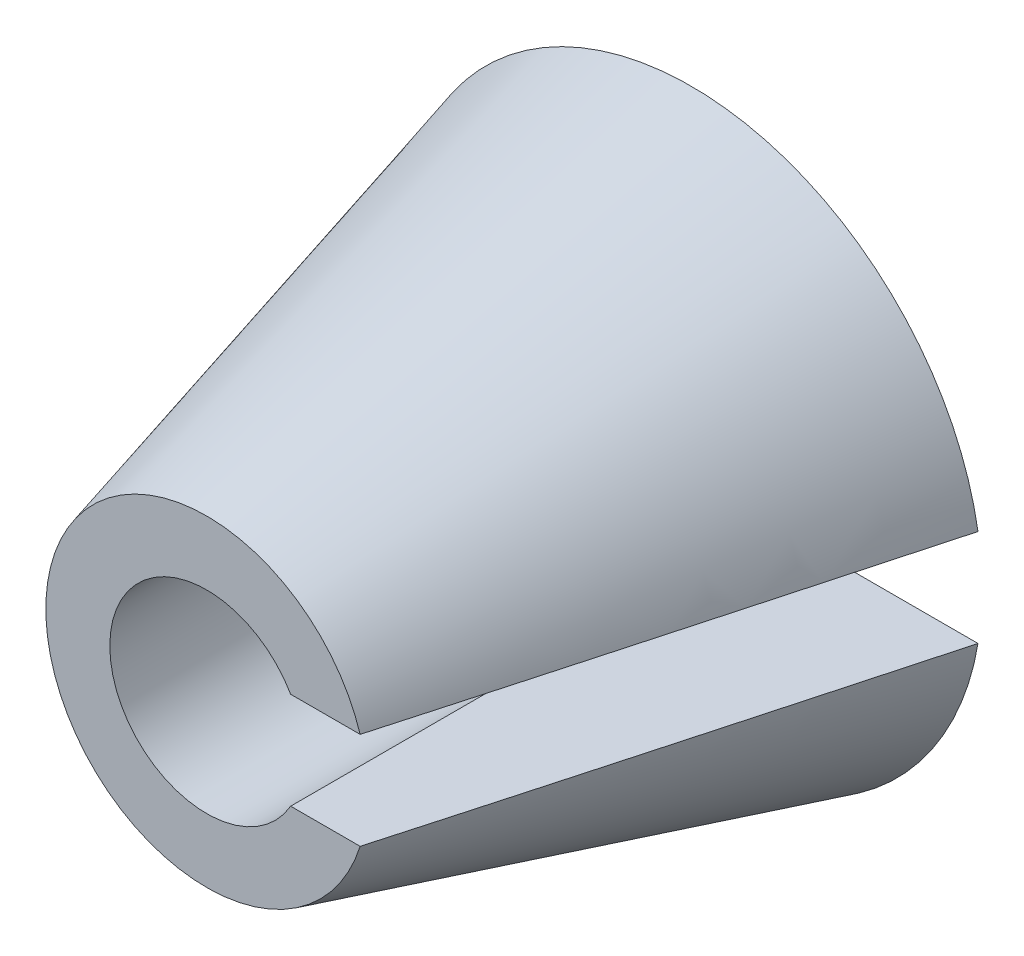
SolidWorks part; units mm, degrees
ref_plane "Front Plane" through (0, 0, 0) normal (0, 0, 1) x (1, 0, 0)
ref_plane "Top Plane" through (0, 0, 0) normal (0, 1, 0) x (1, 0, 0)
ref_plane "Right Plane" through (0, 0, 0) normal (1, 0, 0) x (0, 0, -1)
sketch "Sketch1" plane through (0, 0, 0) normal (0, 0, 1) x (1, 0, 0)
  circle A0 centre (0, 0) radius 6
  dimension "D1" = 12
extrude "Boss-Extrude1" add sketch "Sketch1" along normal blind 10 draft 15
sketch "Sketch2" plane through (0, 0, 0) normal (0, 0, -1) x (-1, 0, 0)
  circle A0 centre (0, 0) radius 2
  dimension "D1" = 4
extrude "Cut-Extrude1" cut sketch "Sketch2" against normal through all
sketch "Sketch3" plane through (0, 0, 0) normal (0, 0, -1) x (-1, 0, 0)
  line L1 (-1.7321, 1) -> (-6, 1)
  line L2 (-1.7321, 1) -> (-1.7321, -1)
  line L3 (-1.7321, -1) -> (-6, -1)
  line L4 (-6, 1) -> (-6, -1)
  circle A0 centre (0, 0) radius 2 construction
  circle A1 centre (0, 0) radius 6 construction
  point P4 (-1.7321, 0)
  dimension "D1" = 2
extrude "Cut-Extrude2" cut sketch "Sketch3" against normal through all
